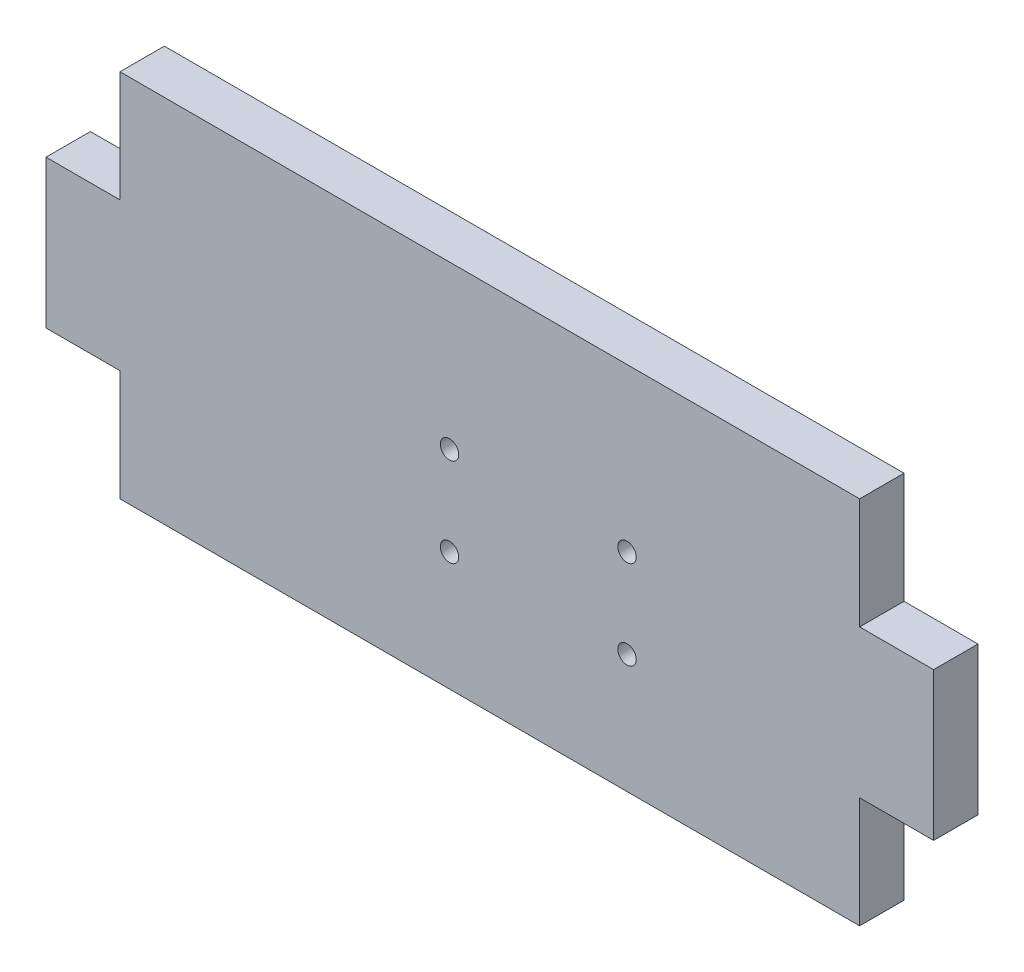
SolidWorks part; units mm, degrees
ref_plane "Plan de face" through (0, 0, 0) normal (0, 0, 1) x (1, 0, 0)
ref_plane "Plan de dessus" through (0, 0, 0) normal (0, 1, 0) x (1, 0, 0)
ref_plane "Plan de droite" through (0, 0, 0) normal (1, 0, 0) x (0, 0, -1)
sketch "Esquisse1" plane through (0, 0, 0) normal (0, 0, 1) x (1, 0, 0)
  line L1 (0, 0) -> (100, 0)
  line L2 (0, 0) -> (0, 50)
  line L3 (0, 50) -> (100, 50)
  line L4 (100, 0) -> (100, 50)
  line L5 (0, 35) -> (-10, 35)
  line L6 (0, 35) -> (0, 15)
  line L7 (0, 15) -> (-10, 15)
  line L8 (-10, 35) -> (-10, 15)
  line L9 (100, 35) -> (110, 35)
  line L10 (100, 35) -> (100, 15)
  line L11 (100, 15) -> (110, 15)
  line L12 (110, 35) -> (110, 15)
  point P13 (-10, 25)
  point P14 (0, 25)
  point P15 (110, 25)
  point P16 (100, 25)
  dimension "D1" = 100
  dimension "D2" = 50
  dimension "D3" = 10
  dimension "D4" = 20
  dimension "D5" = 10
  dimension "D6" = 20
extrude "Boss.-Extru.1" add sketch "Esquisse1" along normal blind 6 contours L5 L8 L7 L2 | L1 L4 L3 L2 | L12 L9 L4 L11
sketch "Esquisse2" plane through (0, 0, 0) normal (0, 0, -1) x (-1, 0, 0)
  circle A0 centre (-44.5503, 16.0653) radius 1.25
  circle A1 centre (-44.5503, 28.0653) radius 1.25
  circle A2 centre (-68.5503, 28.0653) radius 1.25
  circle A3 centre (-68.5503, 16.0653) radius 1.25
  dimension "D1" = 2.5
  dimension "D2" = 2.5
  dimension "D3" = 2.5
  dimension "D4" = 2.5
extrude "Enlèv. mat.-Extru.1" cut sketch "Esquisse2" against normal up to surface (6 mm away) up to face at (50, 25, 6)
